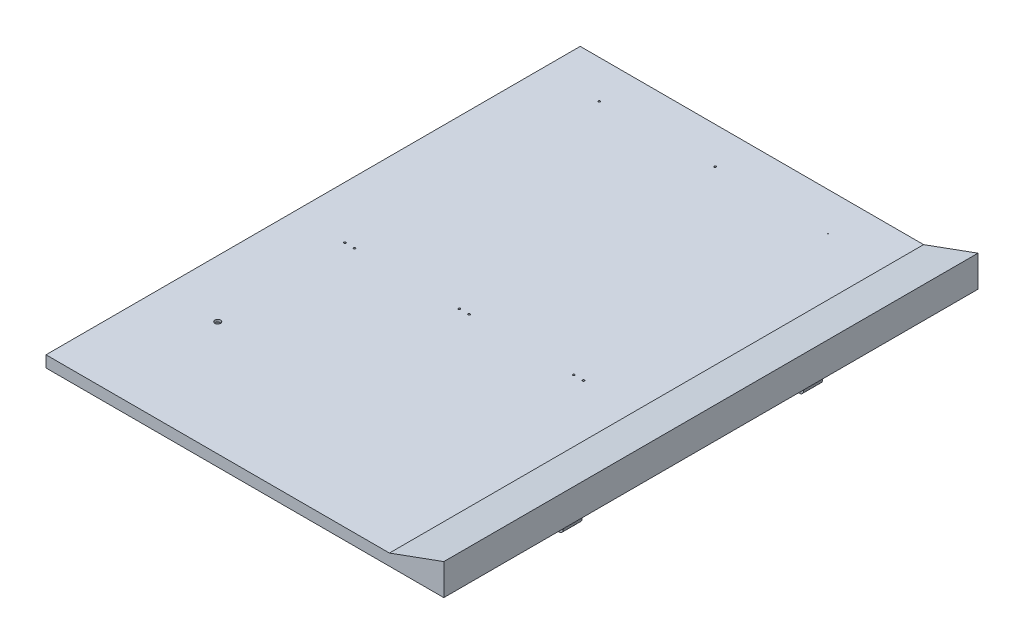
SolidWorks part; units mm, degrees
ref_plane "Front Plane" through (0, 0, 0) normal (0, 0, 1) x (1, 0, 0)
ref_plane "Top Plane" through (0, 0, 0) normal (0, 1, 0) x (1, 0, 0)
ref_plane "Right Plane" through (0, 0, 0) normal (1, 0, 0) x (0, 0, -1)
sketch "Sketch2" plane through (0, 0, 0) normal (0, 0, 1) x (1, 0, 0)
  line L0 (0, 0) -> (0, 81.8658)
  line L1 (0, 81.8658) -> (-142.5, 30)
  line L2 (-142.5, 30) -> (-1042.5, 30)
  line L5 (0, 0) -> (-1042.5, 0)
  line L6 (-1042.5, 0) -> (-1042.5, 30)
  dimension "D1" = 30
  dimension "D2" = 160
  dimension "D3" = 1042.5
  dimension "D4" = 900
extrude "Boss-Extrude1" add sketch "Sketch2" along normal blind 1100 and the other way blind 300
sketch "Sketch3" plane through (0, 0, 0) normal (0, 0, 1) x (1, 0, 0)
  line L0 (-47.5, 0) -> (-47.5, -50)
  line L1 (-1042.5, 0) -> (0, 0) construction
  line L2 (-57.5, -60) -> (-512.5, -60)
  line L3 (-522.5, -50) -> (-522.5, 0)
  line L4 (-522.5, 0) -> (-47.5, 0)
  line L5 (-510, -50) -> (-60, -50) construction
  line L6 (-510, -42.5) -> (-60, -42.5)
  line L7 (-510, -57.5) -> (-60, -57.5)
  line L8 (0, 0) -> (0, 81.8658) construction
  line L9 (-1022.5, 0) -> (-1022.5, -50)
  line L10 (-1012.5, -60) -> (-1007.5, -60)
  line L11 (-997.5, -50) -> (-997.5, 0)
  line L12 (-997.5, 0) -> (-1022.5, 0)
  arc A0 (-510, -42.5) -> (-510, -57.5) centre (-510, -50) ccw
  arc A1 (-60, -57.5) -> (-60, -42.5) centre (-60, -50) ccw
  arc A2 (-512.5, -60) -> (-522.5, -50) centre (-512.5, -50) cw
  arc A3 (-47.5, -50) -> (-57.5, -60) centre (-57.5, -50) cw
  circle A6 centre (-1010, -50) radius 7.5
  arc A7 (-1007.5, -60) -> (-997.5, -50) centre (-1007.5, -50) ccw
  arc A8 (-1022.5, -50) -> (-1012.5, -60) centre (-1012.5, -50) ccw
  point P8 (-285, -50)
  point P17 (-522.5, -60)
  point P20 (-47.5, -60)
  point P29 (-997.5, -60)
  point P32 (-1022.5, -60)
  dimension "D4" = 12.5
  dimension "D5" = 60
  dimension "D7" = 7.5
  dimension "D8" = 10
  dimension "D10" = 50
  dimension "D11" = 15
  dimension "D12" = 10
  dimension "D13" = 12.5
  dimension "D14" = 500
  dimension "D1" = 60
  dimension "D2" = 475
  dimension "D3" = 50
  dimension "D6" = 450
  dimension "D9" = 25
  dimension "D15" = 60
extrude "Boss-Extrude2" add sketch "Sketch3" along normal blind 800
sketch "Sketch5" plane through (0, 30, 0) normal (0, 1, 0) x (1, 0, 0)
  line L0 (-1042.5, -1100) -> (-142.5, -1100) construction
  line L1 (-142.5, -1100) -> (-142.5, 300) construction
  circle A0 centre (-892.5, -800) radius 7.5
  dimension "D1" = 15
  dimension "D2" = 300
  dimension "D3" = 750
extrude "Cut-Extrude2" cut sketch "Sketch5" against normal through all
sketch "Sketch9" plane through (-47.5, 0, 0) normal (1, 0, 0) x (0, 0, -1)
  line L0 (-690, 0) -> (-690, -60)
  line L1 (300, 0) -> (-1100, 0) construction
  line L2 (-800, -60) -> (0, -60) construction
  line L3 (-690, -60) -> (-110, -60)
  line L4 (-110, -60) -> (-110, 0)
  line L5 (-800, 0) -> (0, 0) construction
  line L6 (-110, 0) -> (-690, 0)
  line L7 (-740, -50) -> (-740, -60)
  line L8 (-740, -60) -> (-800, -60)
  line L9 (0, -50) -> (0, 0) construction
  line L10 (-800, -60) -> (-800, -50)
  line L12 (-800, -50) -> (0, -50) construction
  line L13 (0, 0) -> (0, -60)
  line L14 (0, -60) -> (-60, -60)
  line L15 (-740, -50) -> (-740, 0)
  line L16 (-740, 0) -> (-800, 0)
  line L17 (-800, -50) -> (-800, 0) construction
  line L18 (-800, 0) -> (-800, -50)
  line L19 (-60, -60) -> (-60, 0)
  line L20 (-60, 0) -> (0, 0)
  dimension "D1" = 580
  dimension "D2" = 110
  dimension "D3" = 60
  dimension "D4" = 50
  dimension "D5" = 60
  dimension "5" = 50
extrude "Cut-Extrude5" cut sketch "Sketch9" against normal through all
sketch "Sketch6" plane through (0, 0, 0) normal (0, -1, 0) x (1, 0, 0)
  line L1 (-905, 816) -> (-880, 816)
  line L2 (-905, 816) -> (-905, 784)
  line L3 (-905, 784) -> (-880, 784)
  line L4 (-880, 816) -> (-880, 784)
  line L5 (-905, 816) -> (-880, 784) construction
  line L6 (-905, 784) -> (-880, 816) construction
  point P0 (-892.5, 800)
  dimension "D1" = 32
  dimension "D2" = 25
extrude "Boss-Extrude3" add sketch "Sketch6" along normal blind 37.5
sketch "Sketch7" plane through (0, 0, 816) normal (0, 0, 1) x (1, 0, 0)
  line L0 (-880, 0) -> (-905, 0) construction
  line L1 (-900.5, 0) -> (-884.5, 0)
  line L2 (-900.5, 0) -> (-900.5, -32.5)
  line L3 (-900.5, -32.5) -> (-884.5, -32.5)
  line L4 (-884.5, 0) -> (-884.5, -32.5)
  line L5 (-905, -37.5) -> (-905, 0) construction
  dimension "D1" = 4.5
  dimension "D2" = 16
  dimension "D3" = 32.5
extrude "Cut-Extrude3" cut sketch "Sketch7" against normal through all
sketch "Sketch8" plane through (0, 0, 0) normal (0, -1, 0) x (1, 0, 0)
  line L0 (-900.5, 784) -> (-900.5, 816) construction
  line L1 (-900.5, 768) -> (-884.5, 768)
  line L2 (-900.5, 768) -> (-900.5, 832)
  line L3 (-900.5, 832) -> (-884.5, 832)
  line L4 (-884.5, 768) -> (-884.5, 832)
  line L5 (-900.5, 768) -> (-884.5, 832) construction
  line L6 (-900.5, 832) -> (-884.5, 768) construction
  point P0 (-892.5, 800)
  dimension "D1" = 0
  dimension "D2" = 64
extrude "Cut-Extrude4" cut sketch "Sketch8" against normal blind 24
sketch "Sketch10" plane through (0, 30, 0) normal (0, 1, 0) x (1, 0, 0)
  line L0 (-1042.5, -500) -> (-142.5, -500) construction
  line L1 (-1042.5, 300) -> (-1042.5, -1100) construction
  line L2 (-142.5, 300) -> (-142.5, -1100) construction
  line L3 (-892.5, -500) -> (-892.5, 300) construction
  line L4 (-142.5, 300) -> (-1042.5, 300) construction
  line L5 (-592.5, -500) -> (-592.5, 300) construction
  line L6 (-292.5, -500) -> (-292.5, 300) construction
  line L7 (-142.5, -1100) -> (-1042.5, -1100) construction
  line L8 (-892.5, 200) -> (-292.5, 200) construction
  line L9 (-905.2, -454.05) -> (-879.8, -454.05) construction
  line L10 (-879.8, -454.05) -> (-605.2, -454.05) construction
  line L11 (-605.2, -454.05) -> (-579.8, -454.05) construction
  line L12 (-579.8, -454.05) -> (-413.5459, -454.05) construction
  line L13 (-413.5459, -454.05) -> (-279.8, -454.05) construction
  circle A0 centre (-892.5, 200) radius 2.5908
  circle A1 centre (-592.5, 203.743) radius 2.5908
  circle A2 centre (-292.5, 200) radius 1.02
  circle A3 centre (-905.2, -454.05) radius 2.5908
  circle A4 centre (-879.8, -454.05) radius 2.5908
  circle A5 centre (-605.2, -454.05) radius 2.5908
  circle A6 centre (-579.8, -454.05) radius 2.5908
  circle A7 centre (-305.2, -454.05) radius 2.5908
  circle A8 centre (-279.8, -454.05) radius 2.5908
  dimension "D6" = 5.1816
  dimension "D7" = 5.1816
  dimension "D8" = 12.7
  dimension "D10" = 5.1816
  dimension "D11" = 5.1816
  dimension "D13" = 25.4
  dimension "D14" = 5.1816
  dimension "D15" = 5.1816
  dimension "D17" = 25.4
  dimension "D18" = 5.1816
  dimension "D19" = 5.1816
  dimension "D20" = 2.04
  dimension "D1" = 150
  dimension "D2" = 300
  dimension "D3" = 300
  dimension "D4" = 600
  dimension "D5" = 700
  dimension "D9" = 25.4
  dimension "D12" = 12.7
  dimension "D16" = 12.7
  dimension "D21" = 654.05
extrude "Cut-Extrude6" cut sketch "Sketch10" against normal blind 20
